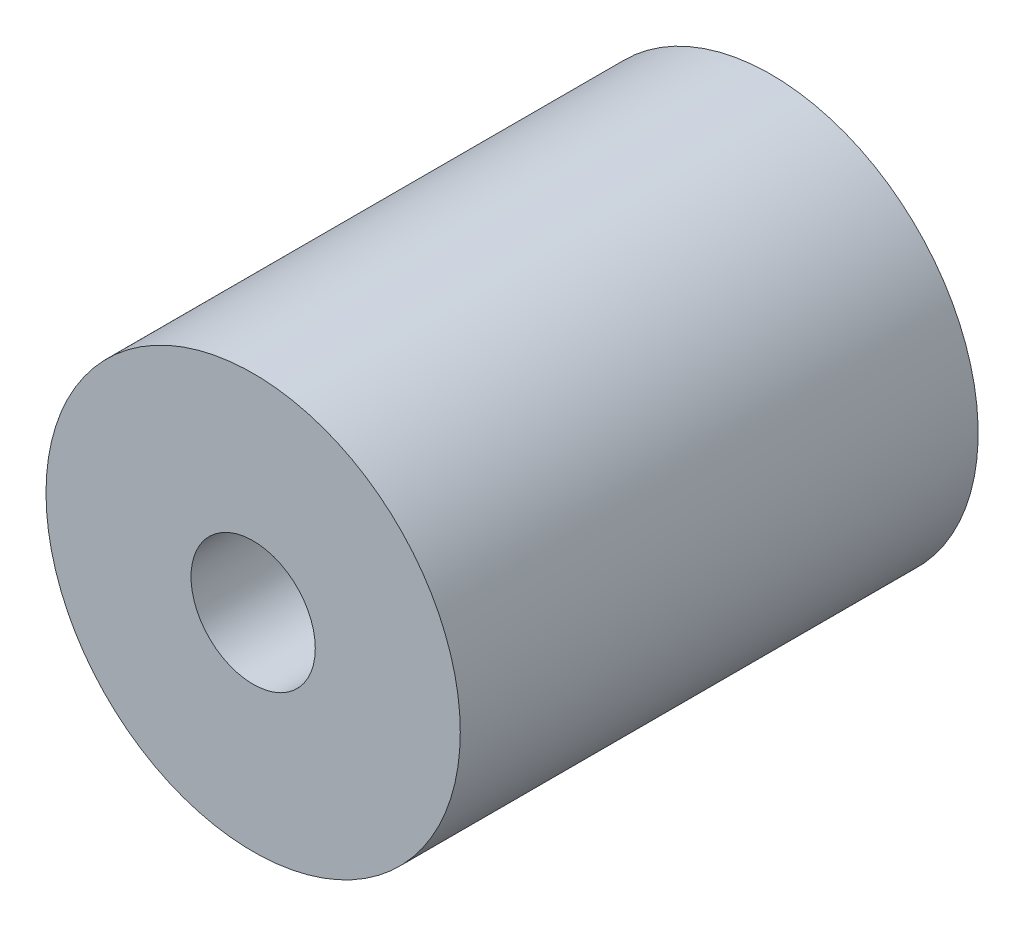
SolidWorks part; units mm, degrees
ref_plane "Front Plane" through (0, 0, 0) normal (0, 0, 1) x (1, 0, 0)
ref_plane "Top Plane" through (0, 0, 0) normal (0, 1, 0) x (1, 0, 0)
ref_plane "Right Plane" through (0, 0, 0) normal (1, 0, 0) x (0, 0, -1)
sketch "Sketch1" plane through (0, 0, 0) normal (0, 0, 1) x (1, 0, 0)
  circle A0 centre (0, 0) radius 3
  circle A1 centre (0, 0) radius 10
  dimension "D1" = 6
  dimension "D2" = 20
extrude "Boss-Extrude1" add sketch "Sketch1" along normal blind 10
sketch "Sketch4" plane through (0, 0, 0) normal (0, 0, -1) x (-1, 0, 0)
  circle A0 centre (0, 0) radius 10
extrude "Boss-Extrude3" add sketch "Sketch4" along normal blind 5
sketch "Sketch5" plane through (0, 0, -5) normal (0, 0, -1) x (-1, 0, 0)
  circle A0 centre (0, 0) radius 10
  circle A1 centre (0, 0) radius 3
  dimension "D1" = 6
  dimension "D2" = 20
extrude "Boss-Extrude4" add sketch "Sketch5" along normal blind 10
